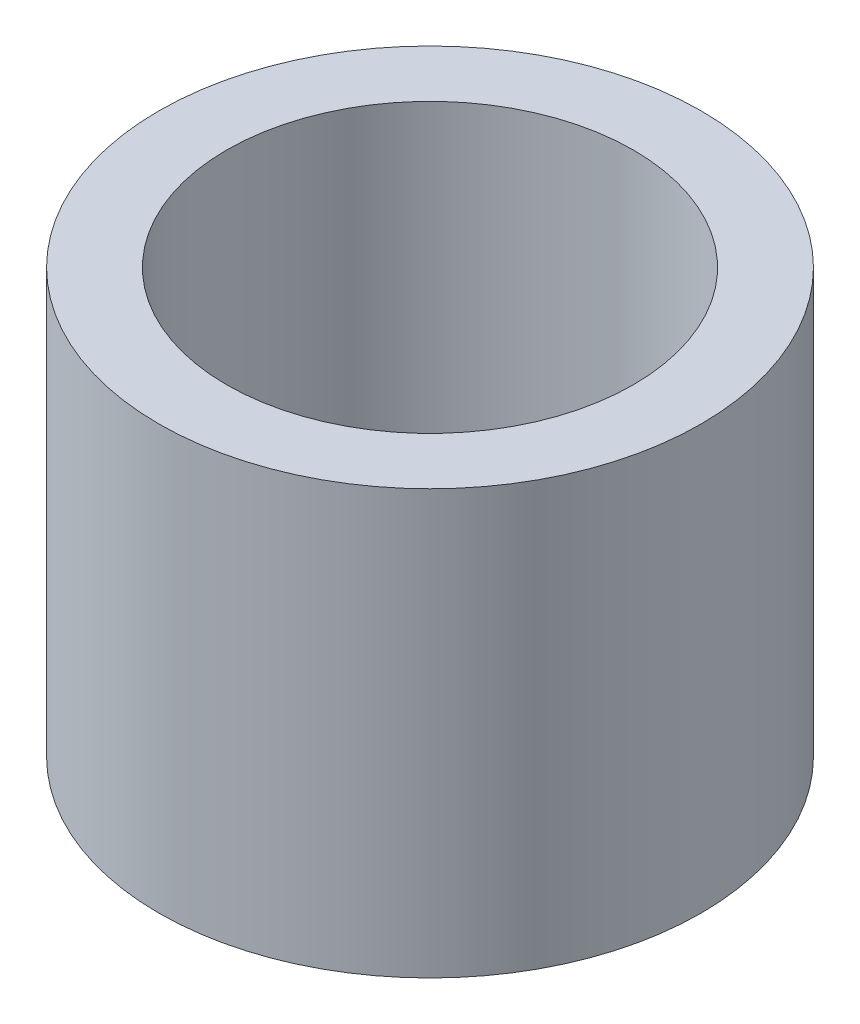
SolidWorks part; units mm, degrees
material "Polyurethane Foam Flexible"
ref_plane "Front" through (0, 0, 0) normal (0, 0, 1) x (1, 0, 0)
ref_plane "Top" through (0, 0, 0) normal (0, 1, 0) x (1, 0, 0)
ref_plane "Right" through (0, 0, 0) normal (1, 0, 0) x (0, 0, -1)
sketch "Sketch1" plane through (0, 0, 0) normal (0, 1, 0) x (1, 0, 0)
  circle A0 centre (0, 0) radius 12
  circle A1 centre (0, 0) radius 16
extrude "Boss-Extrude1" add sketch "Sketch1" along normal blind 25
